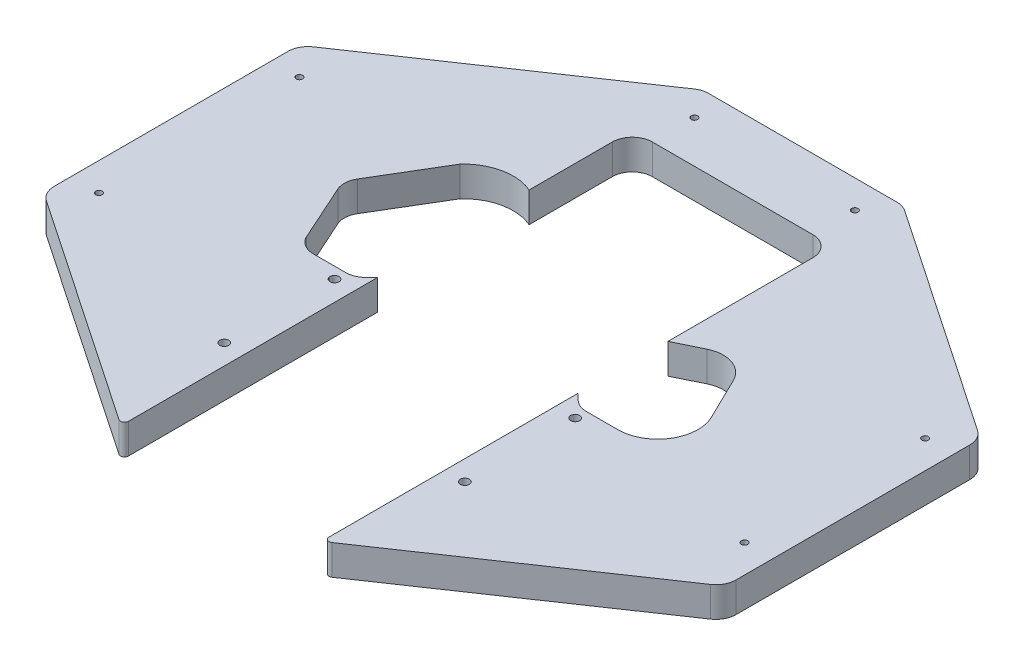
SolidWorks part; units mm, degrees
material "Balsa"
ref_plane "Plan de face" through (0, 0, 0) normal (0, 0, 1) x (1, 0, 0)
ref_plane "Plan de dessus" through (0, 0, 0) normal (0, 1, 0) x (1, 0, 0)
ref_plane "Plan de droite" through (0, 0, 0) normal (1, 0, 0) x (0, 0, -1)
sketch "Esquisse1" plane through (0, 0, 0) normal (0, 1, 0) x (1, 0, 0)
  line L0 (-76.6432, -51.4013) -> (63.3568, 43.5987)
  line L1 (63.3568, 43.5987) -> (163.3568, 43.5987)
  line L2 (-76.6432, -51.4013) -> (-76.6432, -151.4013)
  line L3 (63.3568, -246.4013) -> (163.3568, -246.4013)
  line L4 (303.3568, -51.4013) -> (303.3568, -151.4013)
  line L5 (163.3568, 43.5987) -> (303.3568, -51.4013)
  line L6 (163.3568, -246.4013) -> (303.3568, -151.4013)
  line L7 (-76.6432, -151.4013) -> (63.3568, -246.4013)
  point P0 (-76.6432, 43.5987)
  point P1 (303.3568, -246.4013)
  point P2 (-76.6432, -246.4013)
  point P3 (303.3568, 43.5987)
  dimension "D1" = 380
  dimension "D2" = 290
  dimension "D3" = 140
  dimension "D4" = 95
  dimension "D5" = 140
  dimension "D6" = 95
  dimension "D7" = 140
  dimension "D8" = 95
  dimension "D9" = 95
  dimension "D10" = 140
extrude "Boss.-Extru.1" add sketch "Esquisse1" along normal blind 15 contours L0 L1 L5 L4 L6 L3 L7 L2
sketch "Esquisse6" plane through (0, 0, 246.4013) normal (0, 0, 1) x (1, 0, 0)
  line L1 (63.3568, 15) -> (163.3568, 15)
  line L2 (63.3568, 15) -> (63.3568, 0)
  line L3 (63.3568, 0) -> (163.3568, 0)
  line L4 (163.3568, 15) -> (163.3568, 0)
extrude "Enlèv. mat.-Extru.1" cut sketch "Esquisse6" against normal blind 255
sketch "Esquisse11" plane through (0, 15, 0) normal (0, 1, 0) x (1, 0, 0)
  line L0 (63.3568, 8.5987) -> (63.3568, -246.4013) construction
  line L1 (163.3568, 8.5987) -> (163.3568, -246.4013) construction
  circle A0 centre (53.3568, -129.9013) radius 2.25
  circle A1 centre (53.3568, -184.9013) radius 2.25
  circle A2 centre (173.3568, -129.9013) radius 2.25
  circle A3 centre (173.3568, -184.9013) radius 2.25
  dimension "D1" = 4.5
  dimension "D2" = 4.5
  dimension "D6" = 4.5
  dimension "D7" = 4.5
  dimension "D3" = 55
  dimension "D4" = 10
  dimension "D5" = 55
  dimension "D8" = 10
  dimension "D9" = 10
  dimension "D10" = 10
  dimension "D11" = 61.5
  dimension "D12" = 61.5
sketch "Esquisse8" plane through (0, 15, 0) normal (0, 1, 0) x (1, 0, 0)
  line L4 (63.3568, 8.5987) -> (63.3568, -246.4013) construction
  line L5 (163.3568, 8.5987) -> (163.3568, -246.4013) construction
  circle A0 centre (180.3568, -120.9013) radius 2.25
  circle A1 centre (180.3568, -81.9013) radius 2.25
  circle A2 centre (46.3568, -120.9013) radius 2.25
  circle A3 centre (46.3568, -81.9013) radius 2.25
  dimension "D1" = 4.5
  dimension "D3" = 4.5
  dimension "D11" = 4.5
  dimension "D12" = 4.5
  dimension "D2" = 17
  dimension "D4" = 125.5
  dimension "D5" = 39
  dimension "D7" = 125.5
  dimension "D8" = 17
  dimension "D9" = 39
  dimension "D13" = 17
  dimension "D14" = 17
extrude "Enlèv. mat.-Extru.10" cut sketch "Esquisse11" against normal up to next
extrude "Enlèv. mat.-Extru.11" cut sketch "Esquisse8" against normal up to next
fillet "Congé10" radius 10 8 edges at (303.3568, 7.5, 151.4013) (303.3568, 7.5, 51.4013) (163.3568, 7.5, -43.5987) (63.3568, 7.5, -43.5987) (-76.6432, 7.5, 51.4013) (-76.6432, 7.5, 151.4013) (163.3568, 7.5, -8.5987) (63.3568, 7.5, -8.5987)
fillet "Congé11" radius 2 2 edges at (63.3568, 7.5, 246.4013) (163.3568, 7.5, 246.4013)
sketch "Esquisse12" plane through (0, 15, 0) normal (0, 1, 0) x (1, 0, 0)
  line L0 (34.9402, -48.9186) -> (15.7933, -80.9352)
  line L1 (15.2567, -90.1718) -> (27.9436, -118.3619)
  line L2 (64.8248, -43.5729) -> (63.3568, -59.5923)
  line L3 (63.3568, -1.4013) -> (63.3568, -242.6272) construction
  line L4 (60.4279, -121.3289) -> (63.3568, -118.4)
  line L5 (166.2857, -121.3289) -> (163.3568, -118.4)
  line L7 (37.0627, -124.2578) -> (53.3568, -124.2578)
  line L8 (63.3568, -118.4) -> (63.3568, -59.5923)
  line L9 (173.3568, -124.2578) -> (188.9489, -124.2578)
  line L10 (163.3568, -1.4013) -> (163.3568, -242.6272) construction
  line L11 (206.9248, -95.4904) -> (196.5197, -74.1568)
  line L12 (176.4622, -67.2505) -> (163.3568, -73.6424)
  line L13 (163.3568, -73.6424) -> (163.3568, -118.4)
  arc A0 (27.9436, -118.3619) -> (37.0627, -124.2578) centre (37.0627, -114.2578) ccw
  arc A1 (15.7933, -80.9352) -> (15.2567, -90.1718) centre (24.3757, -86.0678) ccw
  arc A2 (188.9489, -124.2578) -> (206.9248, -95.4904) centre (188.9489, -104.2578) ccw
  arc A3 (196.5197, -74.1568) -> (176.4622, -67.2505) centre (183.0378, -80.7324) ccw
  arc A4 (60.4279, -121.3289) -> (53.3568, -124.2578) centre (53.3568, -114.2578) cw
  arc A5 (173.3568, -124.2578) -> (166.2857, -121.3289) centre (173.3568, -114.2578) cw
  arc A7 (64.8248, -43.5729) -> (34.9402, -48.9186) centre (53.3568, -65.6688) ccw
  point P23 (63.3568, -1.4013)
  point P26 (163.3568, -124.2578)
  point P29 (63.3568, -124.2578)
  circle M3 centre (180.3568, -81.9013) radius 2.25
  circle M4 centre (180.3568, -120.9013) radius 2.25
  line M15 (163.3568, -1.4013) -> (163.3568, -242.6272)
  dimension "D1" = 10
  dimension "D2" = 20
  dimension "D3" = 15
extrude "Enlèv. mat.-Extru.12" cut sketch "Esquisse12" against normal up to next contours L11 L12 L9 M15 M3 M4 | L0 A1 L1 A0 L7 A4 L4 L8 L2 A7
sketch "Esquisse13" plane through (0, 15, 0) normal (0, 1, 0) x (1, 0, 0)
  line L0 (-76.6432, -56.7006) -> (-76.6432, -146.1021) construction
  line L1 (-56.6432, -173.4853) -> (-76.6432, -173.4853)
  line L2 (-56.6432, -173.4853) -> (-56.6432, -30.4519)
  line L3 (-56.6432, -30.4519) -> (-76.6432, -30.4519)
  line L4 (-76.6432, -173.4853) -> (-76.6432, -30.4519)
  line L5 (303.3568, -56.7006) -> (303.3568, -146.1021) construction
  line L6 (283.3568, -10.4047) -> (303.3568, -10.4047)
  line L7 (283.3568, -10.4047) -> (283.3568, -191.7134)
  line L8 (283.3568, -191.7134) -> (303.3568, -191.7134)
  line L9 (303.3568, -10.4047) -> (303.3568, -191.7134)
  dimension "D1" = 20
  dimension "D2" = 0
  dimension "D3" = 20
  dimension "D4" = 0
extrude "Enlèv. mat.-Extru.13" cut sketch "Esquisse13" against normal up to next
fillet "Congé12" radius 10 4 edges at (283.3568, 7.5, 37.8299) (283.3568, 7.5, 164.9728) (-56.6432, 7.5, 37.8299) (-56.6432, 7.5, 164.9728)
sketch "Esquisse14" plane through (0, 15, 0) normal (0, 1, 0) x (1, 0, 0)
  line L0 (-56.6432, -159.6735) -> (-56.6432, -43.1291) construction
  line L1 (283.3568, -43.1291) -> (283.3568, -159.6735) construction
  line L2 (66.4294, 43.5987) -> (160.2843, 43.5987) construction
  circle A0 centre (-42.6432, -51.4035) radius 1.6
  circle A1 centre (-42.6432, -151.4035) radius 1.6
  circle A2 centre (73.3593, 29.5987) radius 1.6
  circle A3 centre (153.3593, 29.5987) radius 1.6
  circle A4 centre (269.3568, -51.3991) radius 1.6
  circle A5 centre (269.3568, -141.3991) radius 1.6
  dimension "D1" = 3.2
  dimension "D2" = 3.2
  dimension "D3" = 3.2
  dimension "D4" = 3.2
  dimension "D5" = 3.2
  dimension "D6" = 3.2
  dimension "D16" = 14
  dimension "D7" = 14
  dimension "D8" = 14
  dimension "D9" = 100
  dimension "D10" = 8.27
  dimension "D11" = 14
  dimension "D12" = 14
  dimension "D13" = 90
  dimension "D14" = 8.27
  dimension "D15" = 80
  dimension "D17" = 14
  dimension "D18" = 6.925
extrude "Enlèv. mat.-Extru.14" cut sketch "Esquisse14" against normal up to next contours A2 | A3 | A4 | A0 | A1 | A5
equation "\"D10@Esquisse14\"=(116.54-100)/2"
equation "\"D14@Esquisse14\"=8.27"
equation "\"D18@Esquisse14\"=(93.85-80)/2"
